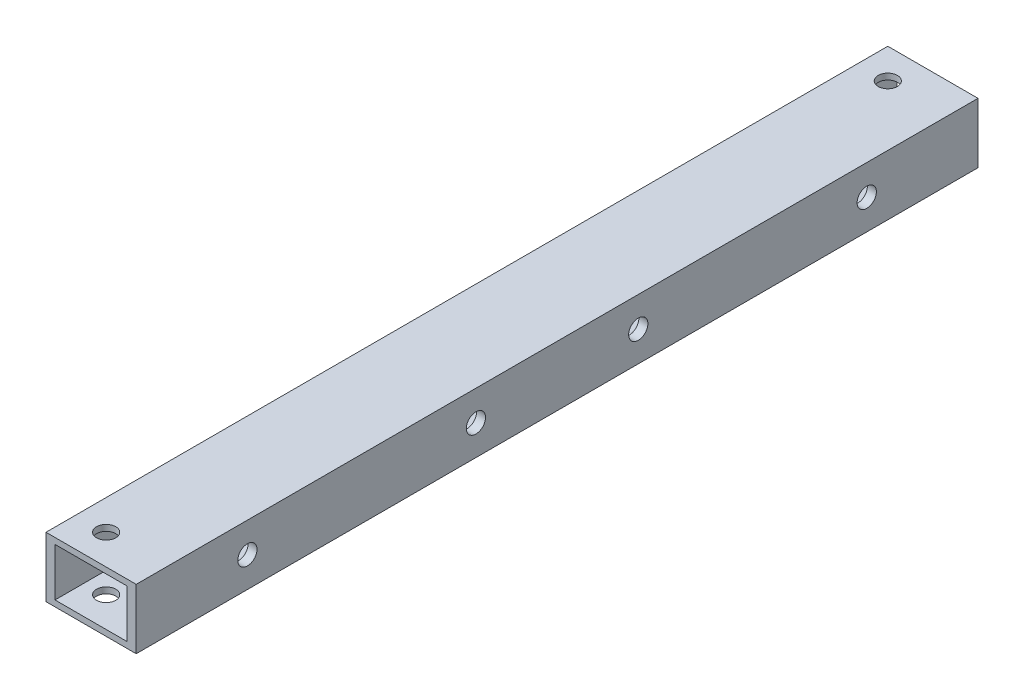
SolidWorks part; units mm, degrees
ref_plane "正面" through (0, 0, 0) normal (0, 0, 1) x (1, 0, 0)
ref_plane "平面" through (0, 0, 0) normal (0, 1, 0) x (1, 0, 0)
ref_plane "右側面" through (0, 0, 0) normal (1, 0, 0) x (0, 0, -1)
sketch "ｽｹｯﾁ1" plane through (0, 0, 0) normal (0, 0, 1) x (1, 0, 0)
  line L1 (-7.5, -5) -> (7.5, -5)
  line L2 (-7.5, -5) -> (-7.5, 5)
  line L3 (-7.5, 5) -> (7.5, 5)
  line L4 (7.5, -5) -> (7.5, 5)
  line L5 (-7.5, -5) -> (7.5, 5) construction
  line L6 (-7.5, 5) -> (7.5, -5) construction
  line L7 (-6, -4) -> (6, -4)
  line L8 (-6, -4) -> (-6, 4)
  line L9 (-6, 4) -> (6, 4)
  line L10 (6, -4) -> (6, 4)
  line L11 (-6, -4) -> (6, 4) construction
  line L12 (-6, 4) -> (6, -4) construction
  point P0 (0, 0)
  point P6 (0, 0)
  dimension "D1" = 1
  dimension "D2" = 15
  dimension "D3" = 10
extrude "ﾎﾞｽ - 押し出し1" add sketch "ｽｹｯﾁ1" along normal blind 70
sketch "ｽｹｯﾁ2" plane through (7.5, 0, 0) normal (1, 0, 0) x (0, 0, -1)
  line L0 (-70, -5) -> (0, -5) construction
  line L1 (0, -5) -> (0, 5) construction
  circle A0 centre (-13.5, 0) radius 1.6
  dimension "D1" = 3.2
  dimension "D2" = 5
  dimension "D3" = 13.5
extrude "ｶｯﾄ - 押し出し1" cut sketch "ｽｹｯﾁ2" against normal through all
sketch "ｽｹｯﾁ3" plane through (0, 5, 0) normal (0, 1, 0) x (1, 0, 0)
  line L0 (7.5, -70) -> (-7.5, -70) construction
  line L1 (-7.5, -70) -> (-7.5, 0) construction
  circle A0 centre (-2.5, -65) radius 1.6
  dimension "D1" = 3.2
  dimension "D2" = 5
  dimension "D3" = 5
extrude "ｶｯﾄ - 押し出し2" cut sketch "ｽｹｯﾁ3" against normal through all
sketch "ｽｹｯﾁ4" plane through (-7.5, 0, 0) normal (-1, 0, 0) x (0, 0, 1)
  line L0 (70, 5) -> (70, -5) construction
  line L1 (70, 5) -> (0, 5) construction
  circle A0 centre (51.5, 0) radius 1.6
  dimension "D1" = 3.2
  dimension "D2" = 18.5
  dimension "D3" = 5
extrude "ｶｯﾄ - 押し出し3" cut sketch "ｽｹｯﾁ4" against normal through all
mirror "ﾐﾗｰ1" about plane through (0, 0, 0) normal (0, 0, -1) of "ｶｯﾄ - 押し出し3", "ｶｯﾄ - 押し出し1", "ﾎﾞｽ - 押し出し1", "ｶｯﾄ - 押し出し2"
